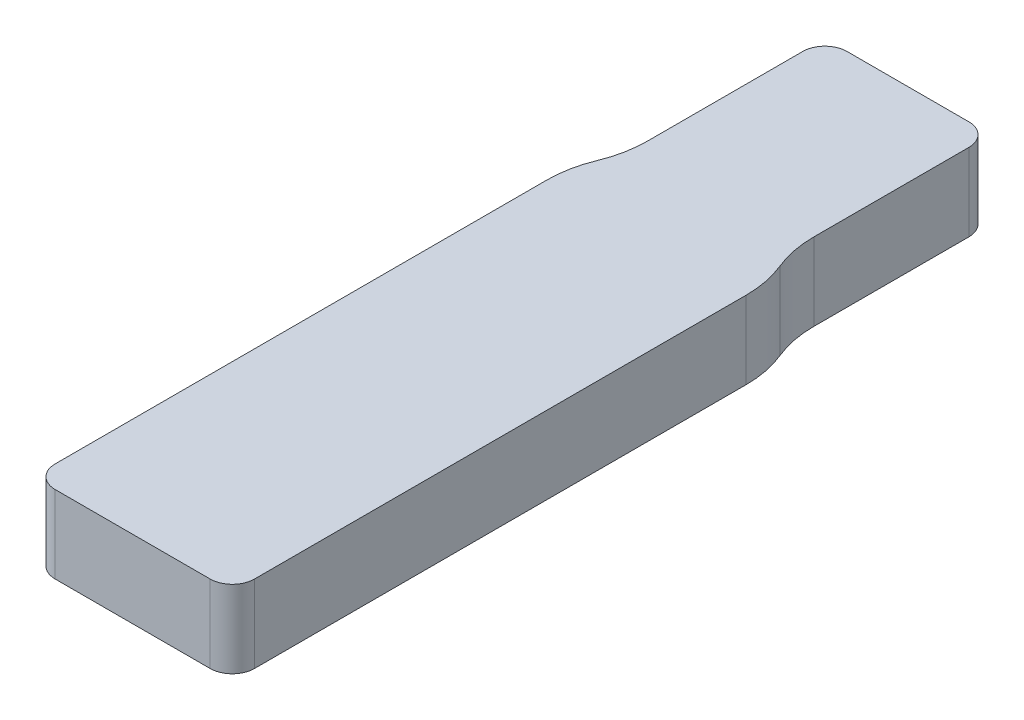
SolidWorks part; units mm, degrees
ref_plane "前视基准面" through (0, 0, 0) normal (0, 0, 1) x (1, 0, 0)
ref_plane "上视基准面" through (0, 0, 0) normal (0, 1, 0) x (1, 0, 0)
ref_plane "右视基准面" through (0, 0, 0) normal (1, 0, 0) x (0, 0, -1)
sketch "草图2" plane through (0, 0, 0) normal (0, 1, 0) x (1, 0, 0)
  line L0 (0, 0) -> (7, 0)
  line L1 (9, 2) -> (9, 46.3928)
  line L2 (0, 70) -> (5.5, 70)
  line L3 (7.5, 68) -> (7.5, 54)
  line L4 (0, 0) -> (-7, 0)
  line L5 (-9, 2) -> (-9, 46.3928)
  line L6 (0, 70) -> (-5.5, 70)
  line L7 (-7.5, 68) -> (-7.5, 54)
  arc A0 (7, 0) -> (9, 2) centre (7, 2) ccw
  arc A1 (7.5, 68) -> (5.5, 70) centre (5.5, 68) ccw
  arc A2 (7.5, 54) -> (8.2515, 50.1888) centre (17.5398, 54) ccw
  arc A3 (9, 46.3928) -> (8.2515, 50.1888) centre (-1, 46.3928) ccw
  arc A4 (-9, 2) -> (-7, 0) centre (-7, 2) ccw
  arc A5 (-5.5, 70) -> (-7.5, 68) centre (-5.5, 68) ccw
  arc A6 (-8.2515, 50.1888) -> (-7.5, 54) centre (-17.5398, 54) ccw
  arc A7 (-8.2515, 50.1888) -> (-9, 46.3928) centre (1, 46.3928) ccw
  dimension "D1" = 0
  dimension "D2" = 0
  dimension "D3" = 44.3928
  dimension "D4" = 44.3928
extrude "凸台-拉伸1" add sketch "草图2" along normal blind 7
